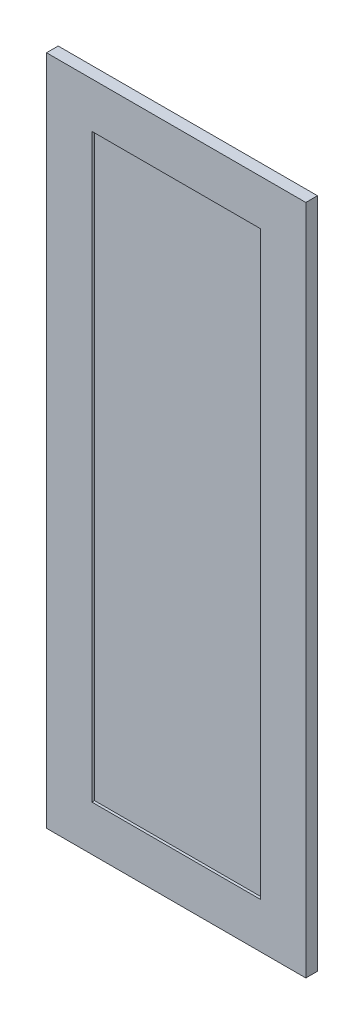
SolidWorks part; units mm, degrees
material "Pine"
ref_plane "Front Plane" through (0, 0, 0) normal (0, 0, 1) x (1, 0, 0)
ref_plane "Top Plane" through (0, 0, 0) normal (0, 1, 0) x (1, 0, 0)
ref_plane "Right Plane" through (0, 0, 0) normal (1, 0, 0) x (0, 0, -1)
sketch "Sketch1" plane through (0, 0, 0) normal (0, 0, 1) x (1, 0, 0)
  line L1 (-200, 518) -> (200, 518)
  line L2 (-200, 518) -> (-200, -518)
  line L3 (-200, -518) -> (200, -518)
  line L4 (200, 518) -> (200, -518)
  line L5 (-200, 518) -> (200, -518) construction
  line L6 (-200, -518) -> (200, 518) construction
  point P0 (0, 0)
  dimension "D1" = 1036
  dimension "D2" = 400
extrude "Boss-Extrude1" add sketch "Sketch1" along normal blind 18
sketch "Sketch2" plane through (0, 0, 18) normal (0, 0, 1) x (1, 0, 0)
  line L0 (-200, 518) -> (-200, -518) construction
  line L1 (-130, 448) -> (130, 448)
  line L2 (-130, 448) -> (-130, -448)
  line L3 (-130, -448) -> (130, -448)
  line L4 (130, 448) -> (130, -448)
  line L5 (-130, 448) -> (130, -448) construction
  line L6 (-130, -448) -> (130, 448) construction
  line L7 (200, 518) -> (-200, 518) construction
  point P0 (0, 0)
  dimension "D1" = 70
  dimension "D2" = 70
extrude "Cut-Extrude1" cut sketch "Sketch2" against normal blind 4
